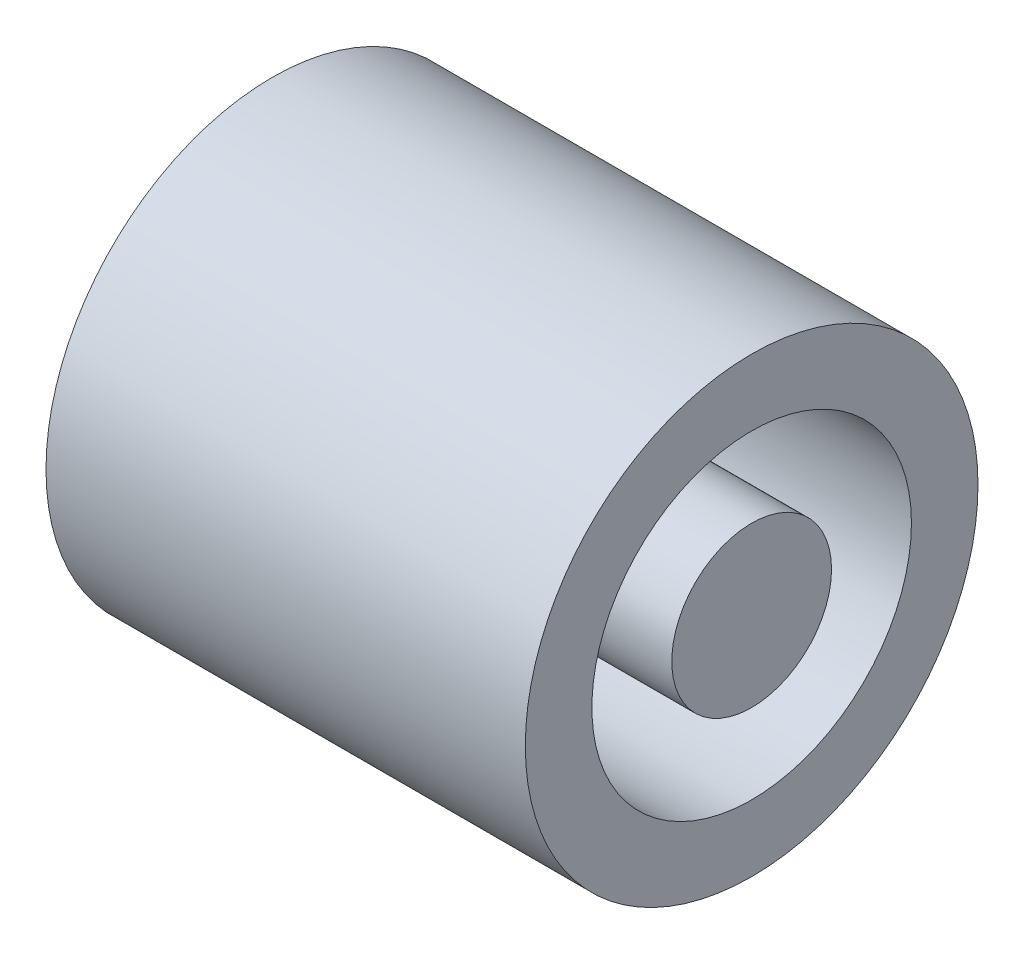
SolidWorks part; units mm, degrees
ref_plane "Front Plane" through (0, 0, 0) normal (0, 0, 1) x (1, 0, 0)
ref_plane "Top Plane" through (0, 0, 0) normal (0, 1, 0) x (1, 0, 0)
ref_plane "Right Plane" through (0, 0, 0) normal (1, 0, 0) x (0, 0, -1)
sketch "Sketch1" plane through (0, 0, 0) normal (1, 0, 0) x (0, 0, -1)
  circle A0 centre (0, 0) radius 8.5
  circle A1 centre (0, 0) radius 6
  dimension "D1" = 17
  dimension "D2" = 12
extrude "Boss-Extrude1" add sketch "Sketch1" along normal blind 18
sketch "Sketch2" plane through (18, 0, 0) normal (1, 0, 0) x (0, 0, -1)
  circle A0 centre (0, 0) radius 3
  dimension "D1" = 6
extrude "Boss-Extrude2" add sketch "Sketch2" against normal blind 18 separate body
